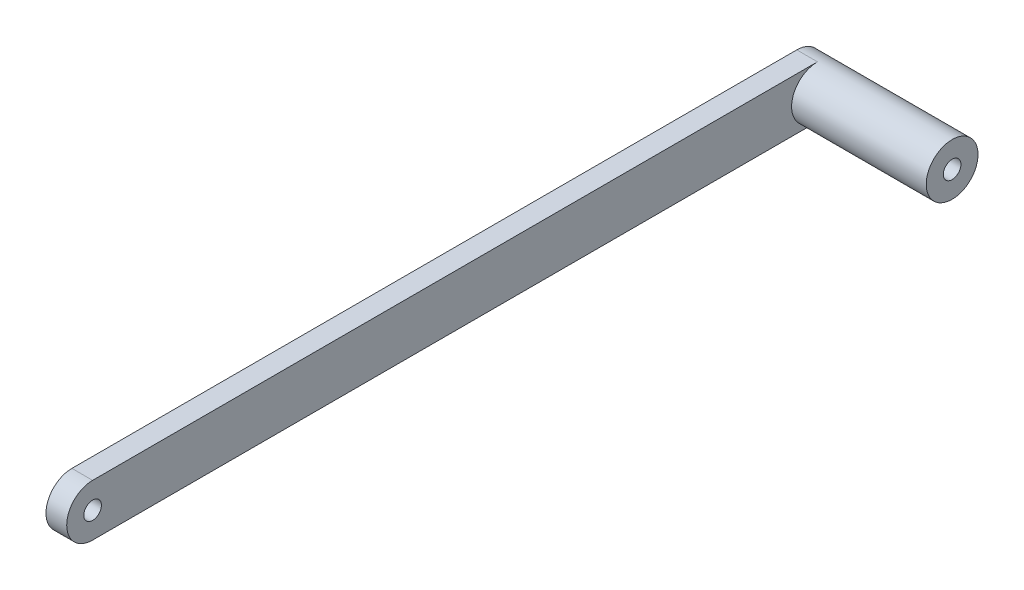
SolidWorks part; units mm, degrees
ref_plane "Plano frontal" through (0, 0, 0) normal (0, 0, 1) x (1, 0, 0)
ref_plane "Plano superior" through (0, 0, 0) normal (0, 1, 0) x (1, 0, 0)
ref_plane "Plano direito" through (0, 0, 0) normal (1, 0, 0) x (0, 0, -1)
sketch "Esboço1" plane through (0, 0, 0) normal (1, 0, 0) x (0, 0, -1)
  line L0 (-35, 0) -> (35, 0) construction
  line L1 (-35, 2.5) -> (35, 2.5)
  line L2 (-35, -2.5) -> (35, -2.5)
  arc A0 (-35, 2.5) -> (-35, -2.5) centre (-35, 0) ccw
  arc A1 (35, -2.5) -> (35, 2.5) centre (35, 0) ccw
  point P2 (0, 0)
  dimension "D1" = 5
  dimension "D2" = 70
extrude "Ressalto-extrusão1" add sketch "Esboço1" along normal blind 2
sketch "Esboço2" plane through (2, 0, 0) normal (1, 0, 0) x (0, 0, -1)
  circle A0 centre (35, 0) radius 2.5
  arc A1 (35, -2.5) -> (35, 2.5) centre (35, 0) ccw construction
extrude "Ressalto-extrusão2" add sketch "Esboço2" along normal blind 13
sketch "Esboço3" plane through (15, 0, 0) normal (1, 0, 0) x (0, 0, -1)
  circle A0 centre (35, 0) radius 0.85
  circle A1 centre (35, 0) radius 2.5 construction
  dimension "D1" = 1.7
extrude "Corte-extrusão1" cut sketch "Esboço3" against normal up to next
sketch "Esboço4" plane through (2, 0, 0) normal (1, 0, 0) x (0, 0, -1)
  circle A0 centre (-35, 0) radius 0.85
  arc A1 (-35, 2.5) -> (-35, -2.5) centre (-35, 0) ccw construction
  dimension "D1" = 1.7
extrude "Corte-extrusão2" cut sketch "Esboço4" against normal up to next
